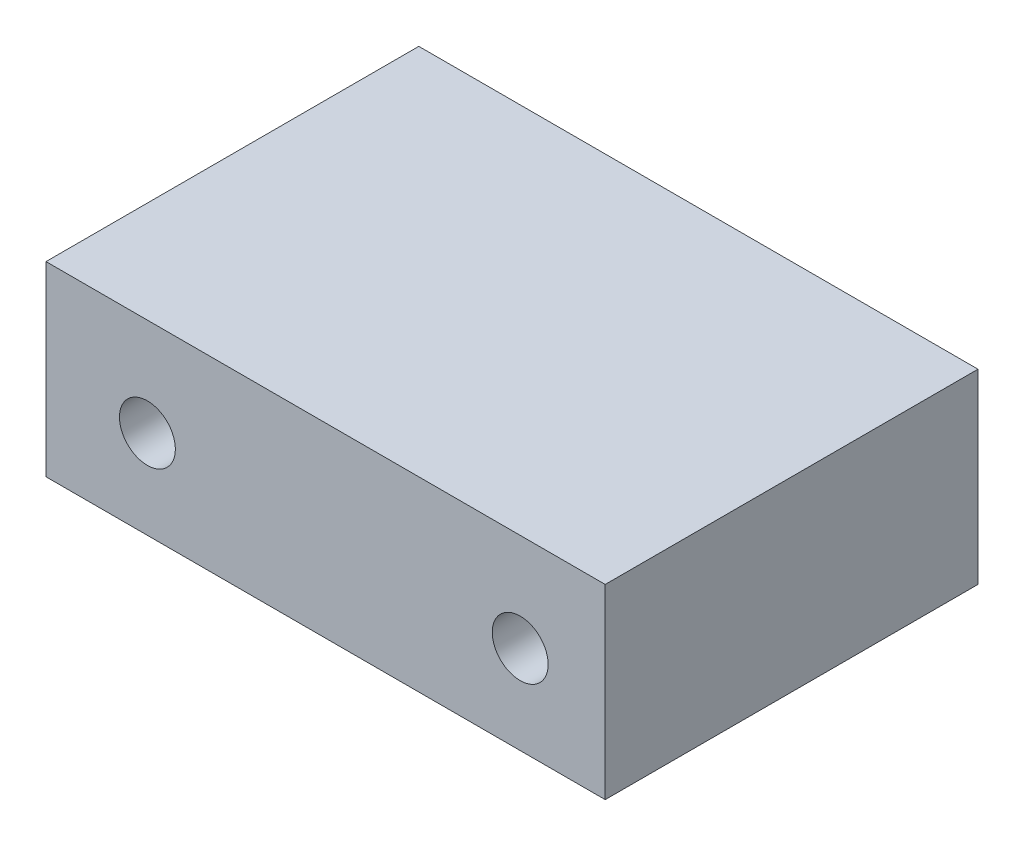
SolidWorks part; units mm, degrees
ref_plane "前视基准面" through (0, 0, 0) normal (0, 0, 1) x (1, 0, 0)
ref_plane "上视基准面" through (0, 0, 0) normal (0, 1, 0) x (1, 0, 0)
ref_plane "右视基准面" through (0, 0, 0) normal (1, 0, 0) x (0, 0, -1)
other "Configuration Table"
sketch "草图1" plane through (0, 0, 0) normal (0, 1, 0) x (1, 0, 0)
  line L1 (-15, -10) -> (15, -10)
  line L2 (-15, -10) -> (-15, 10)
  line L3 (-15, 10) -> (15, 10)
  line L4 (15, -10) -> (15, 10)
  line L5 (-15, -10) -> (15, 10) construction
  line L6 (-15, 10) -> (15, -10) construction
  point P0 (0, 0)
  dimension "D1" = 20
  dimension "D2" = 30
extrude "凸台-拉伸1" add sketch "草图1" along normal blind 10
sketch "草图2" plane through (0, 0, 10) normal (0, 0, 1) x (1, 0, 0)
  circle A0 centre (-9.5601, 4.75) radius 1.5
  circle A1 centre (10.4399, 4.75) radius 1.5
  dimension "D1" = 3
  dimension "D2" = 3
extrude "切除-拉伸1" cut sketch "草图2" against normal blind 25
